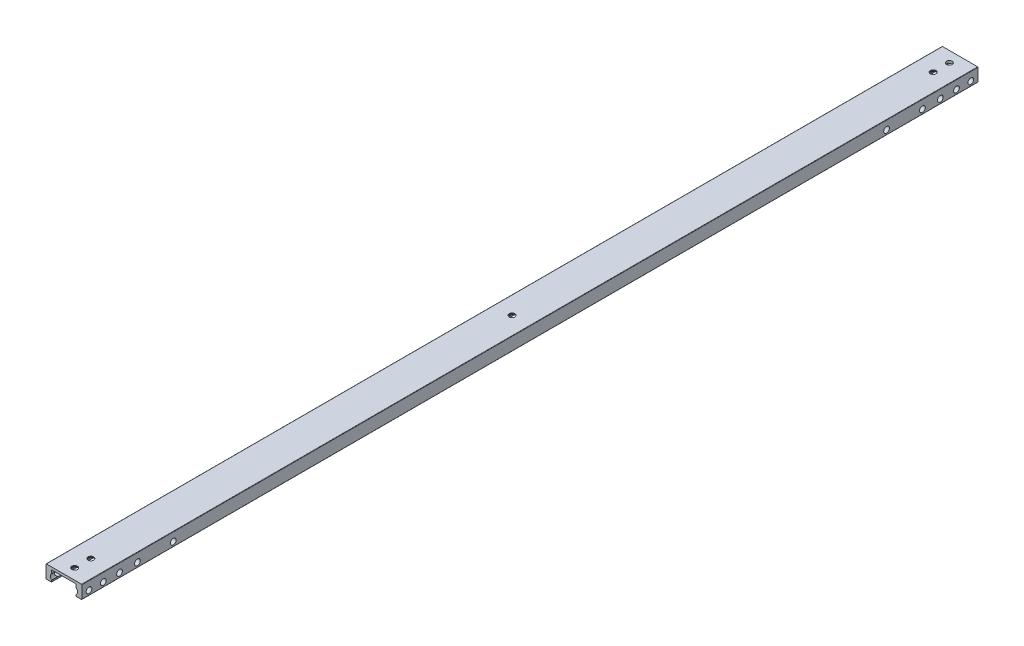
SolidWorks part; units mm, degrees
ref_plane "Front Plane" through (0, 0, 0) normal (0, 0, 1) x (1, 0, 0)
ref_plane "Top Plane" through (0, 0, 0) normal (0, 1, 0) x (1, 0, 0)
ref_plane "Right Plane" through (0, 0, 0) normal (1, 0, 0) x (0, 0, -1)
sketch "Sketch1" plane through (0, 0, 0) normal (0, 0, 1) x (1, 0, 0)
  line L0 (0, 3.7) -> (0, -3.7) construction
  line L1 (-10, -3.7) -> (10, -3.7)
  line L2 (-10, -3.7) -> (-10, 3.7)
  line L3 (-10, 3.7) -> (10, 3.7)
  line L4 (10, -3.7) -> (10, 3.7)
  line L5 (-10, -3.7) -> (10, 3.7) construction
  line L6 (-10, 3.7) -> (10, -3.7) construction
  line L7 (-6.85, -3.7) -> (6.85, -3.7)
  line L8 (-6.85, -3.7) -> (-6.85, 2.3)
  line L9 (-6.85, 2.3) -> (6.85, 2.3)
  line L10 (6.85, -3.7) -> (6.85, 2.3)
  line L11 (0, 2.3) -> (0, -3.7) construction
  point P0 (0, 0)
  dimension "D1" = 20
  dimension "D2" = 7.4
  dimension "D3" = 0
  dimension "D4" = 3.15
  dimension "D5" = 1.4
extrude "Boss-Extrude1" add sketch "Sketch1" along normal blind 500 contours L10 L1 L4 L3 L2 L8 L9
sketch "Sketch4" plane through (0, 2.3, 0) normal (0, -1, 0) x (1, 0, 0)
  line L0 (-10, 250) -> (10, 250) construction
  line L1 (-10, 500) -> (-10, 0) construction
  line L2 (10, 500) -> (10, 0) construction
  line L3 (-6.85, 500) -> (6.85, 500) construction
  circle A0 centre (0, 250) radius 1.6
  circle A1 centre (0, 15) radius 1.6
  circle A2 centre (0, 485) radius 1.6
  circle A3 centre (0, 494) radius 1.6
  circle A4 centre (0, 6) radius 1.6
  dimension "D1" = 3.2
  dimension "D2" = 3.2
  dimension "D4" = 3.2
  dimension "D3" = 235
  dimension "D5" = 6
extrude "Cut-Extrude1" cut sketch "Sketch4" against normal through all
sketch "Sketch5" plane through (0, 0, 500) normal (0, 0, 1) x (1, 0, 0)
  line L0 (0, 3.7) -> (0, -3.7178) construction
  line L1 (-10, 3.7) -> (10, 3.7) construction
  line L2 (-10, -3.7) -> (-6.85, -3.7) construction
  circle A0 centre (-5.7299, -1.15) radius 1.9
  circle A1 centre (5.7299, -1.15) radius 1.9
  dimension "D1" = 3.8
  dimension "D2" = 2.55
extrude "Cut-Extrude2" cut sketch "Sketch5" against normal through all
fillet "Fillet1" radius 0.2 12 edges at (-10, 3.7, 250) (-10, -3.7, 250) (-6.85, -3.7, 250) (-6.85, 0.3848, 250) (-6.85, -2.6848, 250) (-6.85, 2.3, 250) (10, 3.7, 250) (6.85, 2.3, 250) (6.85, -2.6848, 250) (6.85, 0.3848, 250) (6.85, -3.7, 250) (10, -3.7, 250)
sketch "Sketch6" plane through (-6.85, 0, 0) normal (1, 0, 0) x (0, 0, -1)
  line L0 (0, -2.6277) -> (0, 0.3277) construction
  line L1 (0, -2.6277) -> (0, 0.3277)
  line L2 (-250, 3.7) -> (-250, -3.5) construction
  line L3 (-500, 3.7) -> (0, 3.7) construction
  line L4 (-500, -3.5) -> (0, -3.5) construction
  circle A0 centre (-4, -1.15) radius 1.6
  circle A1 centre (-496, -1.15) radius 1.6
  circle A7 centre (-488, -1.15) radius 1.6
  circle A10 centre (-12, -1.15) radius 1.6
  circle A11 centre (-4, -1.15) radius 1.6
  circle A14 centre (-472, -1.15) radius 1.6 [skipped]
  circle A15 centre (-469, -1.15) radius 1.6
  circle A17 centre (-449, -1.15) radius 1.6
  circle A19 centre (-480, -1.15) radius 1.6 [skipped]
  circle A20 centre (-479, -1.15) radius 1.6
  circle A21 centre (-51, -1.15) radius 1.6
  circle A22 centre (-31, -1.15) radius 1.6
  circle A23 centre (-21, -1.15) radius 1.6
  dimension "D1" = 3.2
  dimension "D3" = 4
  dimension "D5" = 3.2
  dimension "D4" = 3.2
  dimension "D7" = 3.2
  dimension "D9" = 8
  dimension "D2" = 4
  dimension "D6" = 10
  dimension "D8" = 20
  dimension "D10" = 9
extrude "Cut-Extrude3" cut sketch "Sketch6" against normal through all and the other way through all contours A0 | A1
chamfer "Chamfer3" distance 1 angle 44 4 edges at (1.6, 2.3, 15) (1.6, 2.3, 250) (-1.6, 2.3, 485) (1.6, 2.3, 494)
